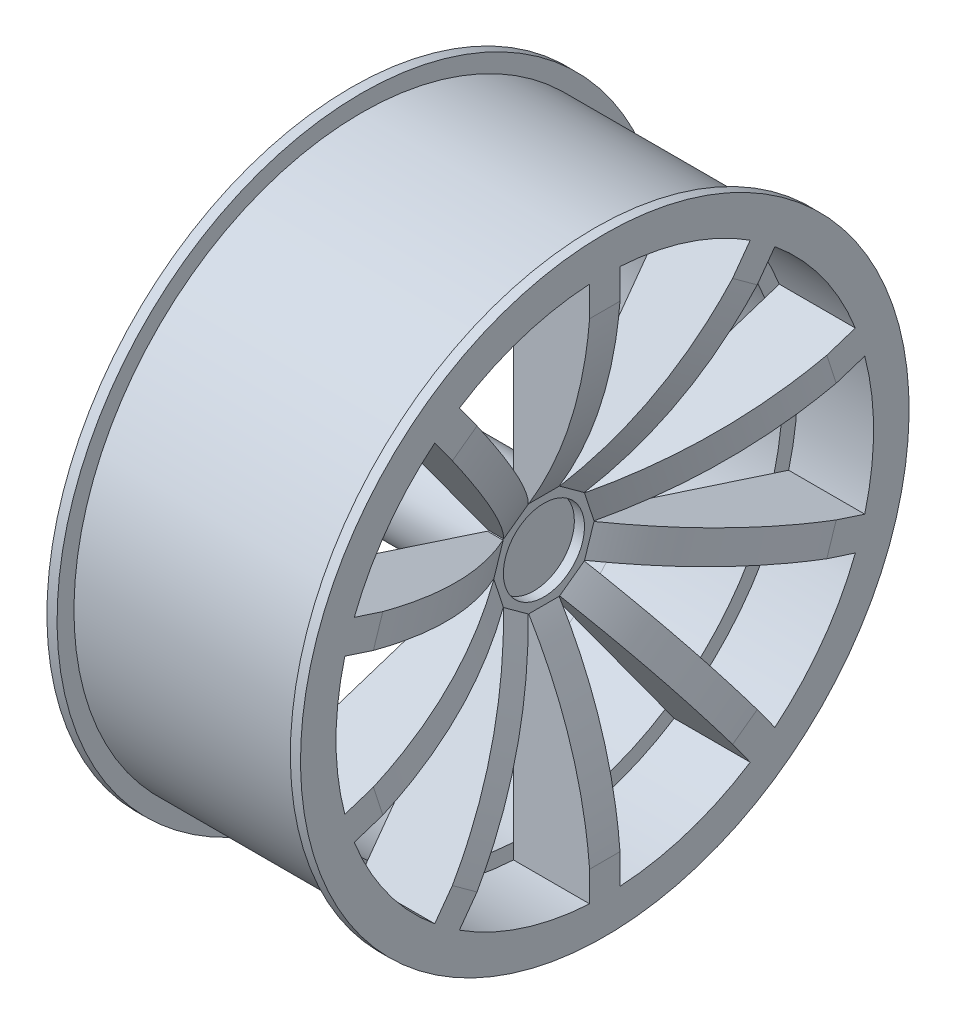
SolidWorks part; units mm, degrees
ref_plane "Alzado" through (0, 0, 0) normal (0, 0, 1) x (1, 0, 0)
ref_plane "Planta" through (0, 0, 0) normal (0, 1, 0) x (1, 0, 0)
ref_plane "Vista lateral" through (0, 0, 0) normal (1, 0, 0) x (0, 0, -1)
sketch "Croquis1" plane through (0, 0, 0) normal (0, 0, 1) x (1, 0, 0)
  line L0 (-11, 28.3334) -> (12, 28.3334)
  line L1 (12, 28.3334) -> (12, 30)
  line L2 (12, 30) -> (13, 30)
  line L3 (13, 30) -> (13, 26.5)
  line L4 (13, 26.5) -> (5.4993, 26.5)
  line L5 (5.4993, 26.5) -> (5.4993, 25)
  line L6 (5.4993, 25) -> (-5.4993, 25)
  line L9 (-12, 30) -> (-11, 30)
  line L10 (-11, 30) -> (-11, 28.3334)
  line L11 (0, 0) -> (0, 25) construction
  line L15 (7, 0) -> (7, 5)
  line L16 (-5.4993, 25) -> (-12, 26.5)
  line L17 (-12, 26.5) -> (-12, 30)
  line L18 (0, 0) -> (13, 0) construction
  line L19 (0, 0) -> (-12, 0) construction
  line L20 (7, 5) -> (-17, 5)
  line L21 (-17, 5) -> (-17, 0)
  line L22 (7, 0) -> (-17, 0)
  line L23 (-17, 0) -> (-38.1159, 0) construction
  dimension "D1" = 25
  dimension "D2" = 5
  dimension "D3" = 12
  dimension "D4" = 13
  dimension "D5" = 1.5
  dimension "D6" = 3.5
  dimension "D7" = 13
  dimension "D8" = 12
  dimension "D9" = 1
  dimension "D10" = 1
  dimension "D11" = 3.5
  dimension "D12" = 5
  dimension "D13" = 7
  dimension "D14" = 17
revolve "Revolución1" add sketch "Croquis1" angle 360 about L23
sketch "Croquis2" plane through (0, 0, 0) normal (0, 0, 1) x (1, 0, 0)
  line L0 (13, 26.5) -> (13, 23.5)
  line L1 (13, -30) -> (13, 30) construction
  line L2 (13, 26.5) -> (5.4993, 26.5)
  line L3 (5.4993, 26.5) -> (5.4993, 4.7)
  line L5 (5.4993, 4.7) -> (7, 4.7)
  line L7 (7, 5) -> (-17, 5) construction
  spline S0 degree 2 poles (13, 23.5) (12.1906, 13.316) (7, 4.7) knots 0 0 0 1 1 1
  dimension "D1" = 3
  dimension "D2" = 0.3
extrude "Saliente-Extruir1" add sketch "Croquis2" along normal mid plane 3
pattern_circular "MatrizC1" count 10 over 360 about axis through (5.4993, 0, 0) along (1, 0, 0) of "Saliente-Extruir1"
sketch "Croquis3" plane through (7, 0, 0) normal (1, 0, 0) x (0, 0, -1)
  circle A0 centre (0, 0) radius 4
  dimension "D1" = 8
extrude "Cortar-Extruir1" cut sketch "Croquis3" against normal blind 1
sketch "Croquis4" plane through (-17, 0, 0) normal (-1, 0, 0) x (0, 0, 1)
  circle A0 centre (0, 0) radius 2.5
  dimension "D1" = 5
extrude "Cortar-Extruir2" cut sketch "Croquis4" against normal blind 5
scale "Scale1" scale about centroid uniform scaling yes scale factor 0.957143
